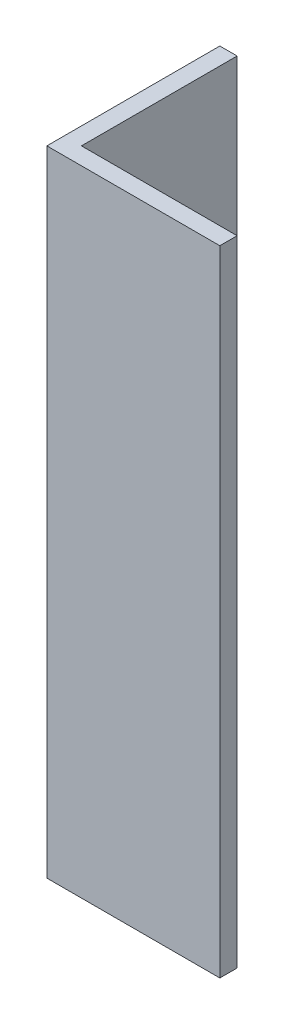
SolidWorks part; units mm, degrees
material "ASTM A36 Steel"
ref_plane "Front Plane" through (0, 0, 0) normal (0, 0, 1) x (1, 0, 0)
ref_plane "Top Plane" through (0, 0, 0) normal (0, 1, 0) x (1, 0, 0)
ref_plane "Right Plane" through (0, 0, 0) normal (1, 0, 0) x (0, 0, -1)
sketch "Sketch1" plane through (0, 0, 0) normal (0, 1, 0) x (1, 0, 0)
  line L0 (0, 0) -> (30, 0)
  line L1 (30, 0) -> (30, 3)
  line L2 (30, 3) -> (3, 3)
  line L3 (3, 3) -> (3, 30)
  line L4 (3, 30) -> (0, 30)
  line L5 (0, 30) -> (0, 0)
extrude "Boss-Extrude1" add sketch "Sketch1" along normal blind 110
